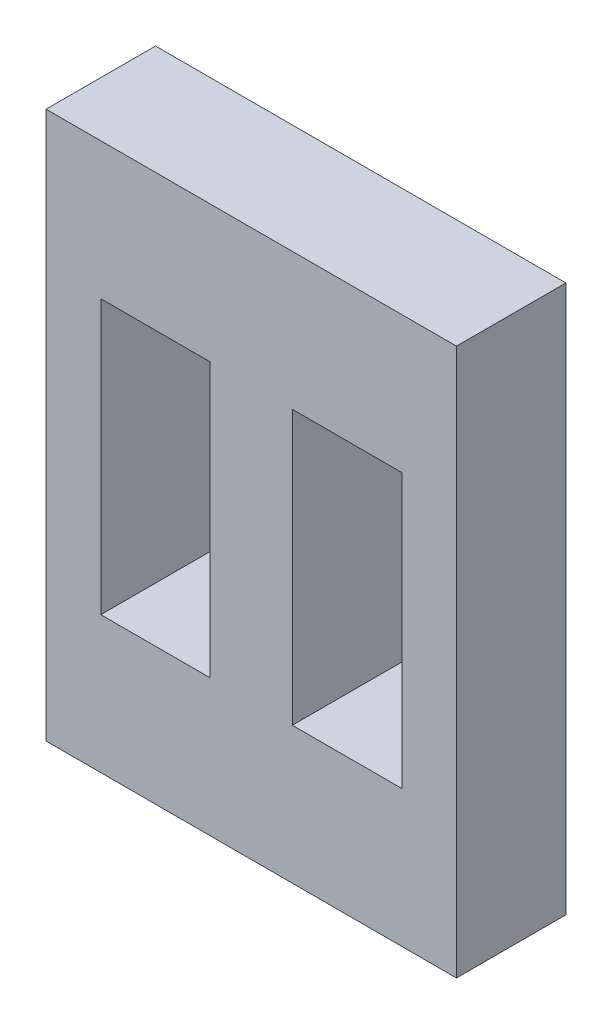
SolidWorks part; units mm, degrees
ref_plane "前视基准面" through (0, 0, 0) normal (0, 0, 1) x (1, 0, 0)
ref_plane "上视基准面" through (0, 0, 0) normal (0, 1, 0) x (1, 0, 0)
ref_plane "右视基准面" through (0, 0, 0) normal (1, 0, 0) x (0, 0, -1)
sketch "草图1" plane through (0, 0, 0) normal (0, 0, 1) x (1, 0, 0)
  line L3 (-46, 0) -> (-37, 0)
  line L4 (-52, 0) -> (-52, 20)
  line L5 (-46, 20) -> (-37, 20)
  line L11 (-46, 5) -> (-50, 5)
  line L12 (-50, 15) -> (-50, 5)
  line L13 (-46, 15) -> (-50, 15)
  line L14 (-46, 15) -> (-46, 5)
  line L29 (-46, 20) -> (-52, 20)
  line L30 (-46, 0) -> (-52, 0)
  line L34 (-43, 15) -> (-39, 15)
  line L35 (-43, 15) -> (-43, 5)
  line L36 (-43, 5) -> (-39, 5)
  line L37 (-39, 15) -> (-39, 5)
  line L41 (-37, 20) -> (-37, 0)
extrude "凸台-拉伸1" add sketch "草图1" along normal mid plane 4
